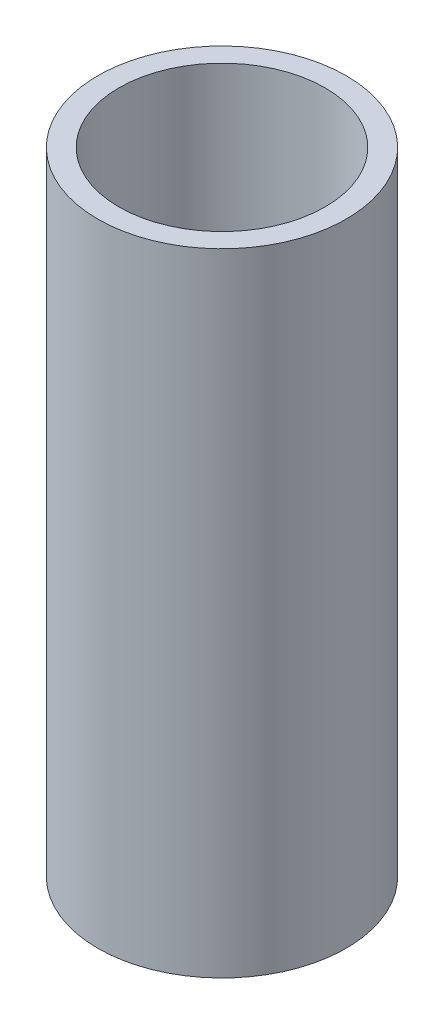
SolidWorks part; units mm, degrees
material "7075-T6 (SN)"
ref_plane "Front Plane" through (0, 0, 0) normal (0, 0, 1) x (1, 0, 0)
ref_plane "Top Plane" through (0, 0, 0) normal (0, 1, 0) x (1, 0, 0)
ref_plane "Right Plane" through (0, 0, 0) normal (1, 0, 0) x (0, 0, -1)
sketch "Sketch1" plane through (0, 0, 0) normal (0, 1, 0) x (1, 0, 0)
  circle A0 centre (0, 0) radius 29.5
  circle A1 centre (0, 0) radius 24.5
  dimension "D1" = 59
  dimension "D2" = 5
extrude "Boss-Extrude1" add sketch "Sketch1" along normal blind 150
